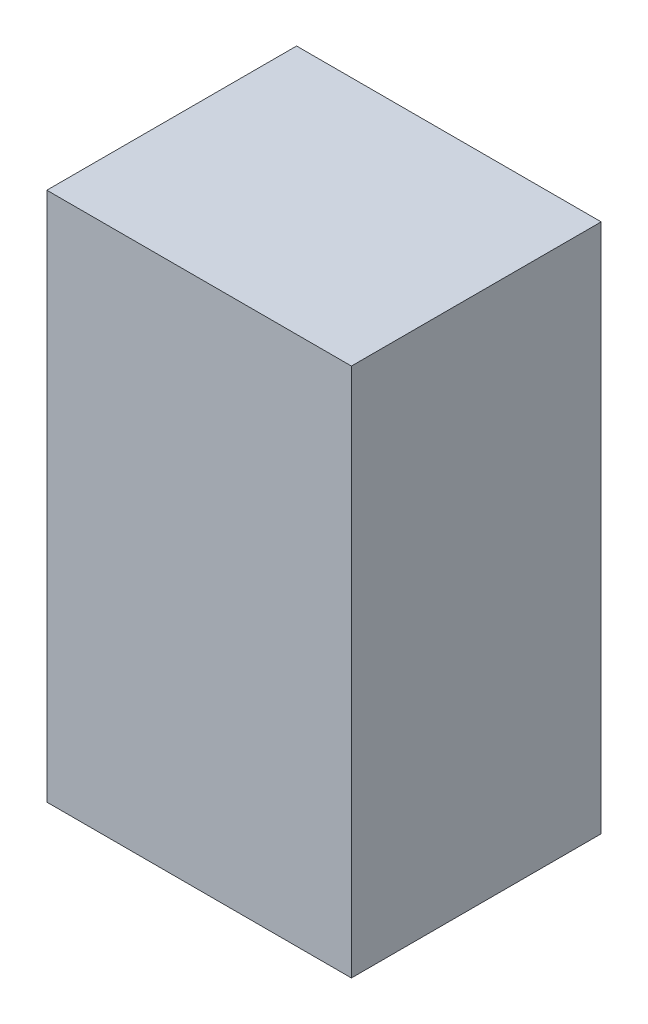
SolidWorks part; units mm, degrees
ref_plane "Front Plane" through (0, 0, 0) normal (0, 0, 1) x (1, 0, 0)
ref_plane "Top Plane" through (0, 0, 0) normal (0, 1, 0) x (1, 0, 0)
ref_plane "Right Plane" through (0, 0, 0) normal (1, 0, 0) x (0, 0, -1)
sketch "Sketch1" plane through (0, 0, 0) normal (0, 0, 1) x (1, 0, 0)
  line L1 (-25, 43.5) -> (25, 43.5)
  line L2 (-25, 43.5) -> (-25, -43.5)
  line L3 (-25, -43.5) -> (25, -43.5)
  line L4 (25, 43.5) -> (25, -43.5)
  line L5 (-25, 43.5) -> (25, -43.5) construction
  line L6 (-25, -43.5) -> (25, 43.5) construction
  point P0 (0, 0)
  dimension "D1" = 50
  dimension "D2" = 87
extrude "Boss-Extrude1" add sketch "Sketch1" along normal blind 41
